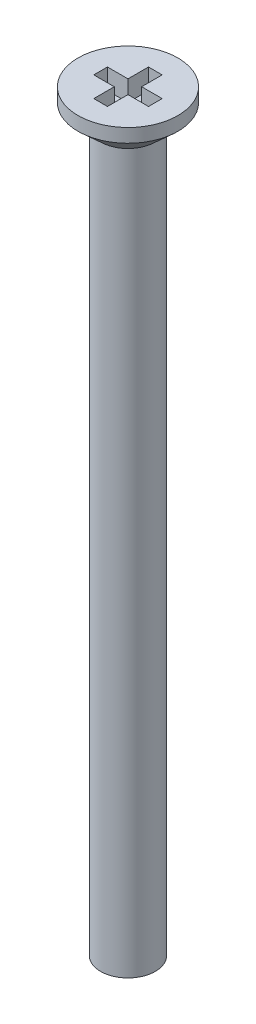
SolidWorks part; units mm, degrees
ref_plane "Front Plane" through (0, 0, 0) normal (0, 0, 1) x (1, 0, 0)
ref_plane "Top Plane" through (0, 0, 0) normal (0, 1, 0) x (1, 0, 0)
ref_plane "Right Plane" through (0, 0, 0) normal (1, 0, 0) x (0, 0, -1)
sketch "Sketch1" plane through (0, 0, 0) normal (0, 0, 1) x (1, 0, 0)
  line L0 (0, 27.93) -> (0, -37.4108) construction
sketch "Sketch2" plane through (0, 0, 0) normal (0, 0, 1) x (1, 0, 0)
  line L0 (0, 2.5) -> (3.65, 2.5)
  line L1 (0, 200027.93) -> (0, -200037.4108) construction
  line L2 (3.65, 2.5) -> (3.65, 1.5)
  line L3 (3.65, 1.5) -> (2, 0)
  line L4 (2, 0) -> (2, -52.5)
  line L5 (2, -52.5) -> (0, -52.5)
  line L6 (0, -52.5) -> (0, 2.5)
  line L7 (0, 0) -> (2, 0) construction
  point P9 (50.0254, 12.0216)
  dimension "D1" = 3.65
  dimension "D2" = 2
  dimension "D3" = 1
  dimension "D4" = 2.5
  dimension "D5" = 55
revolve "Revolve1" add sketch "Sketch2" angle 360 about L0
sketch "Sketch3" plane through (0, 2.5, 0) normal (0, 1, 0) x (1, 0, 0)
  line L0 (-2, 0.5) -> (2, -0.5) construction
  line L1 (-0.5, 2) -> (0.5, 2)
  line L2 (-0.5, 2) -> (-0.5, -2)
  line L3 (-0.5, -2) -> (0.5, -2)
  line L4 (0.5, 2) -> (0.5, -2)
  line L5 (-2, 0.5) -> (2, 0.5)
  line L6 (-2, 0.5) -> (-2, -0.5)
  line L7 (-2, -0.5) -> (2, -0.5)
  line L8 (2, 0.5) -> (2, -0.5)
  line L9 (-0.5, -2) -> (0.5, 2) construction
  dimension "D1" = 1
  dimension "D2" = 4
extrude "Cut-Extrude1" cut sketch "Sketch3" against normal blind 1.5 contours L8 L5 L4 L7 | L2 L5 L4 L1 | L6 L7 L2 L5 | L2 L7 L4 L5 | L7 L2 L3 L4
